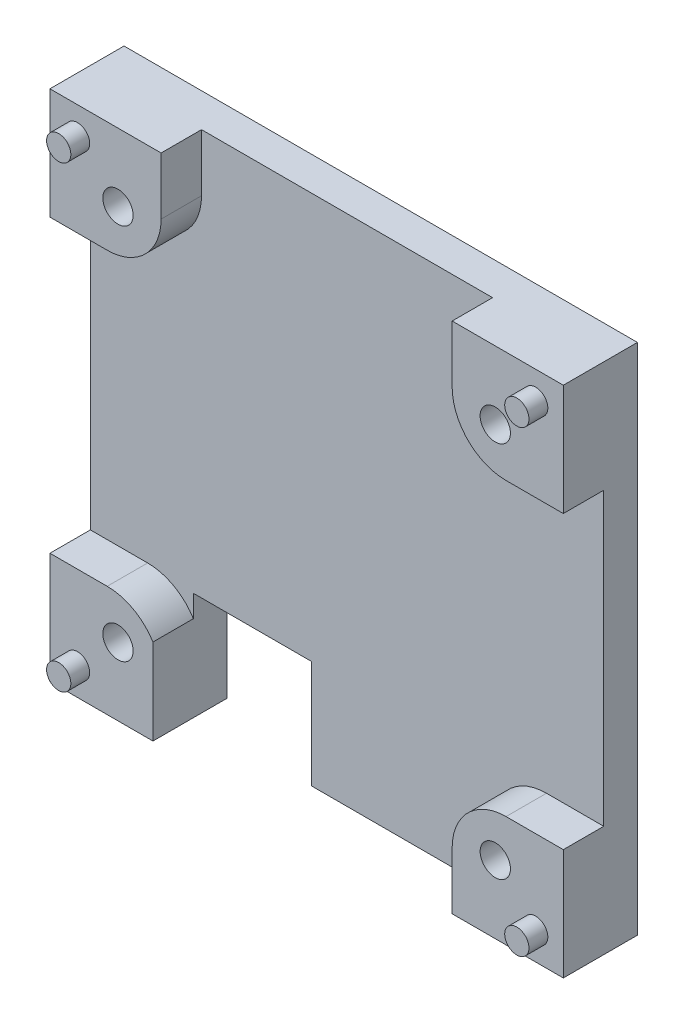
SolidWorks part; units mm, degrees
ref_plane "Front Plane" through (0, 0, 0) normal (0, 0, 1) x (1, 0, 0)
ref_plane "Top Plane" through (0, 0, 0) normal (0, 1, 0) x (1, 0, 0)
ref_plane "Right Plane" through (0, 0, 0) normal (1, 0, 0) x (0, 0, -1)
sketch "Sketch1" plane through (0, 0, 0) normal (0, 0, 1) x (1, 0, 0)
  line L0 (-8.5037, 11.5645) -> (9.4363, 11.5645) construction
  line L1 (-18.5837, -7.4855) -> (19.5163, -7.4855)
  line L2 (-18.5837, -7.4855) -> (-18.5837, 30.6145)
  line L3 (-18.5837, 30.6145) -> (19.5163, 30.6145)
  line L4 (19.5163, -7.4855) -> (19.5163, 30.6145)
  line L5 (-8.5037, 13.5645) -> (9.4363, 13.5645)
  line L6 (-8.5037, 9.5645) -> (9.4363, 9.5645)
  circle A0 centre (-13.5337, 25.5645) radius 1.4
  circle A1 centre (14.4663, 25.5645) radius 1.4
  circle A2 centre (17.4663, 28.5645) radius 1.3
  circle A3 centre (14.4663, -2.4355) radius 1.4
  circle A4 centre (17.4663, -5.4355) radius 1.3
  circle A5 centre (-13.5337, -2.4355) radius 1.4
  circle A6 centre (-16.5337, -5.4355) radius 1.3
  circle A7 centre (-16.5337, 28.5645) radius 1.3
  circle A8 centre (0.4663, 11.5645) radius 6.97
  arc A9 (-8.5037, 13.5645) -> (-8.5037, 9.5645) centre (-8.5037, 11.5645) ccw
  arc A10 (9.4363, 9.5645) -> (9.4363, 13.5645) centre (9.4363, 11.5645) ccw
  point P38 (0.4663, 11.5645)
sketch "Sketch3" plane through (0, 0, 0) normal (0, 0, 1) x (1, 0, 0)
  line L1 (-18.5837, 30.6145) -> (19.5163, 30.6145)
  line L2 (-18.5837, 30.6145) -> (-18.5837, -7.4855)
  line L3 (-18.5837, -7.4855) -> (19.5163, -7.4855)
  line L4 (19.5163, 30.6145) -> (19.5163, -7.4855)
  circle A0 centre (-13.5337, 25.5645) radius 1.125
  circle A1 centre (14.4663, 25.5645) radius 1.125
  circle A2 centre (14.4663, -2.4355) radius 1.125
  circle A3 centre (-13.5337, -2.4355) radius 1.125
  dimension "D1" = 2.25
extrude "Boss-Extrude1" add sketch "Sketch3" against normal blind 2.5
sketch "Sketch2" plane through (0, 0, 0) normal (0, 0, 1) x (1, 0, 0)
  line L1 (-18.5837, 30.6145) -> (-10.3337, 30.6145)
  line L2 (-18.5837, 30.6145) -> (-18.5837, 22.3645)
  line L3 (-18.5837, 22.3645) -> (-14.3337, 22.3645)
  line L4 (-10.3337, 30.6145) -> (-10.3337, 26.3645)
  line L5 (19.5163, 30.6145) -> (11.2663, 30.6145)
  line L6 (19.5163, 30.6145) -> (19.5163, 22.3645)
  line L7 (19.5163, 22.3645) -> (15.2663, 22.3645)
  line L8 (11.2663, 30.6145) -> (11.2663, 26.3645)
  line L9 (19.5163, -7.4855) -> (11.2663, -7.4855)
  line L10 (19.5163, -7.4855) -> (19.5163, 0.7645)
  line L11 (19.5163, 0.7645) -> (15.2663, 0.7645)
  line L12 (11.2663, -7.4855) -> (11.2663, -3.2355)
  line L13 (-18.5837, -7.4855) -> (-10.3337, -7.4855)
  line L14 (-18.5837, -7.4855) -> (-18.5837, 0.7645)
  line L15 (-18.5837, 0.7645) -> (-14.3337, 0.7645)
  line L16 (-10.3337, -7.4855) -> (-10.3337, -3.2355)
  arc A0 (-14.3337, 0.7645) -> (-10.3337, -3.2355) centre (-14.3337, -3.2355) cw
  arc A1 (15.2663, 0.7645) -> (11.2663, -3.2355) centre (15.2663, -3.2355) ccw
  arc A2 (15.2663, 22.3645) -> (11.2663, 26.3645) centre (15.2663, 26.3645) cw
  arc A3 (-14.3337, 22.3645) -> (-10.3337, 26.3645) centre (-14.3337, 26.3645) ccw
  circle A4 centre (-13.5337, 25.5645) radius 1.125
  circle A5 centre (14.4663, 25.5645) radius 1.125
  circle A6 centre (14.4663, -2.4355) radius 1.125
  circle A7 centre (-13.5337, -2.4355) radius 1.125
  dimension "D2" = 4
  dimension "D3" = 2.25
  dimension "D1" = 8.25
extrude "Boss-Extrude2" add sketch "Sketch2" along normal blind 3
sketch "Sketch4" plane through (0, 0, -2.5) normal (0, 0, -1) x (-1, 0, 0)
  line L0 (-0.4663, 11.5645) -> (-0.4663, 30.6145) construction
  line L7 (-0.4663, 30.6145) -> (-0.4663, 11.5645) construction
  line L8 (-0.4663, 11.5645) -> (18.5837, 11.5645) construction
  line L9 (18.5837, -7.4855) -> (18.5837, 30.6145) construction
  line L10 (18.5837, 30.6145) -> (-19.5163, 30.6145) construction
  line L12 (2.1887, 0.5145) -> (10.9387, 0.5145)
  line L13 (2.1887, 0.5145) -> (2.1887, -4.7355)
  line L14 (2.1887, -4.7355) -> (10.9387, -4.7355)
  line L15 (10.9387, 0.5145) -> (10.9387, -4.7355)
  line L17 (6.5637, 0.5145) -> (6.5637, -4.7355) construction
  line L18 (18.5837, -7.4855) -> (-19.5163, -7.4855) construction
  line L19 (10.9387, -2.1105) -> (6.5637, -2.1105) construction
  line L20 (6.5637, -2.1105) -> (2.1887, -2.1105) construction
  point P0 (-0.4663, 11.5645)
  dimension "D2" = 8.75
  dimension "D3" = 12.02
  dimension "D4" = 5.25
  dimension "D5" = 5.375
extrude "Cut-Extrude1" cut sketch "Sketch4" against normal blind 10
sketch "Sketch6" plane through (0, 0, -2.5) normal (0, 0, -1) x (-1, 0, 0)
  line L0 (18.5837, -7.4855) -> (-19.5163, -7.4855) construction
  line L1 (10.9387, -4.7355) -> (2.1887, -4.7355)
  line L2 (10.9387, -4.7355) -> (10.9387, -7.4855)
  line L3 (10.9387, -7.4855) -> (2.1887, -7.4855)
  line L4 (2.1887, -4.7355) -> (2.1887, -7.4855)
  line L5 (2.1887, 0.5145) -> (2.1887, -4.7355) construction
extrude "Cut-Extrude2" cut sketch "Sketch6" against normal blind 10
sketch "Sketch7" plane through (0, 0, 3) normal (0, 0, 1) x (1, 0, 0)
  circle A0 centre (-16.5337, 28.5645) radius 0.9
  circle A1 centre (17.4663, 28.5645) radius 0.9
  circle A2 centre (17.4663, -5.4355) radius 0.9
  circle A3 centre (-16.5337, -5.4355) radius 0.9
  dimension "D1" = 1.8
extrude "Boss-Extrude3" add sketch "Sketch7" along normal blind 1.4
